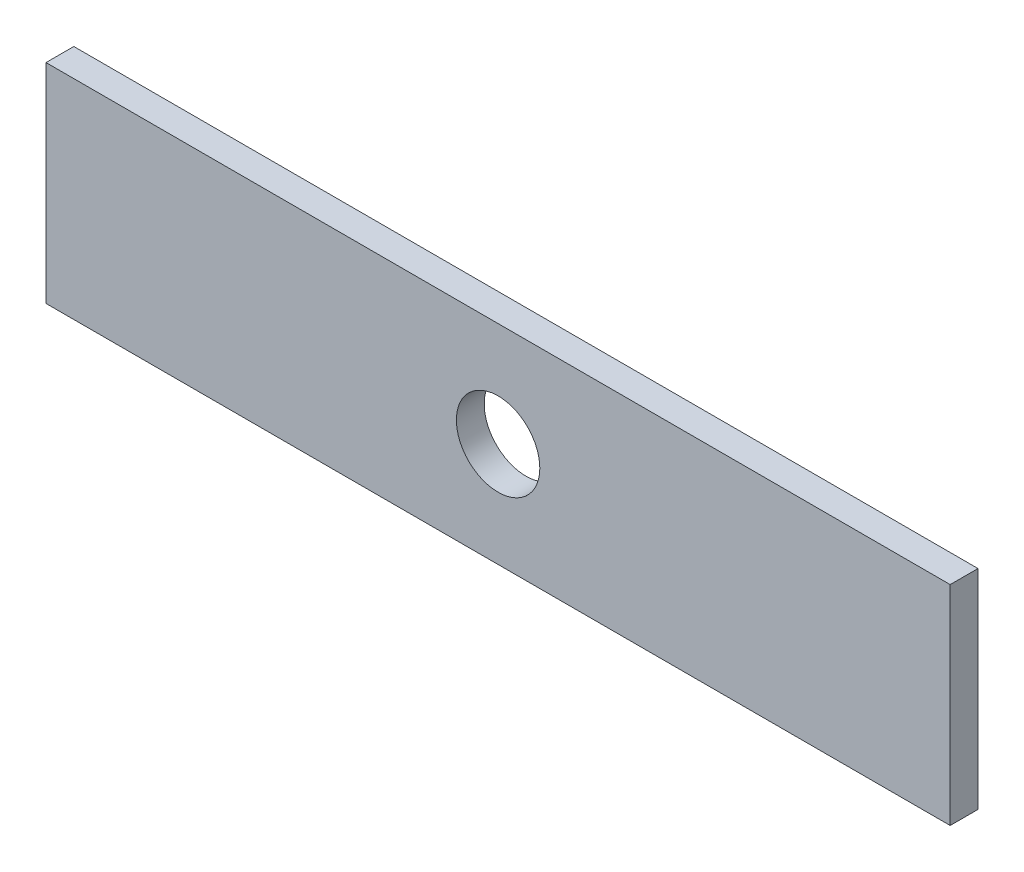
SolidWorks part; units mm, degrees
ref_plane "Plano frontal" through (0, 0, 0) normal (0, 0, 1) x (1, 0, 0)
ref_plane "Plano superior" through (0, 0, 0) normal (0, 1, 0) x (1, 0, 0)
ref_plane "Plano direito" through (0, 0, 0) normal (1, 0, 0) x (0, 0, -1)
sketch "Esboço1" plane through (0, 0, 0) normal (0, 0, 1) x (1, 0, 0)
  line L1 (-30.0557, 16.0262) -> (34.9443, 16.0262)
  line L2 (-30.0557, 16.0262) -> (-30.0557, 1.0262)
  line L3 (-30.0557, 1.0262) -> (34.9443, 1.0262)
  line L4 (34.9443, 16.0262) -> (34.9443, 1.0262)
  circle A0 centre (2.4443, 8.5262) radius 3
  dimension "D4" = 6
  dimension "D1" = 65
  dimension "D2" = 15
extrude "Ressalto-extrusão1" add sketch "Esboço1" along normal blind 2
